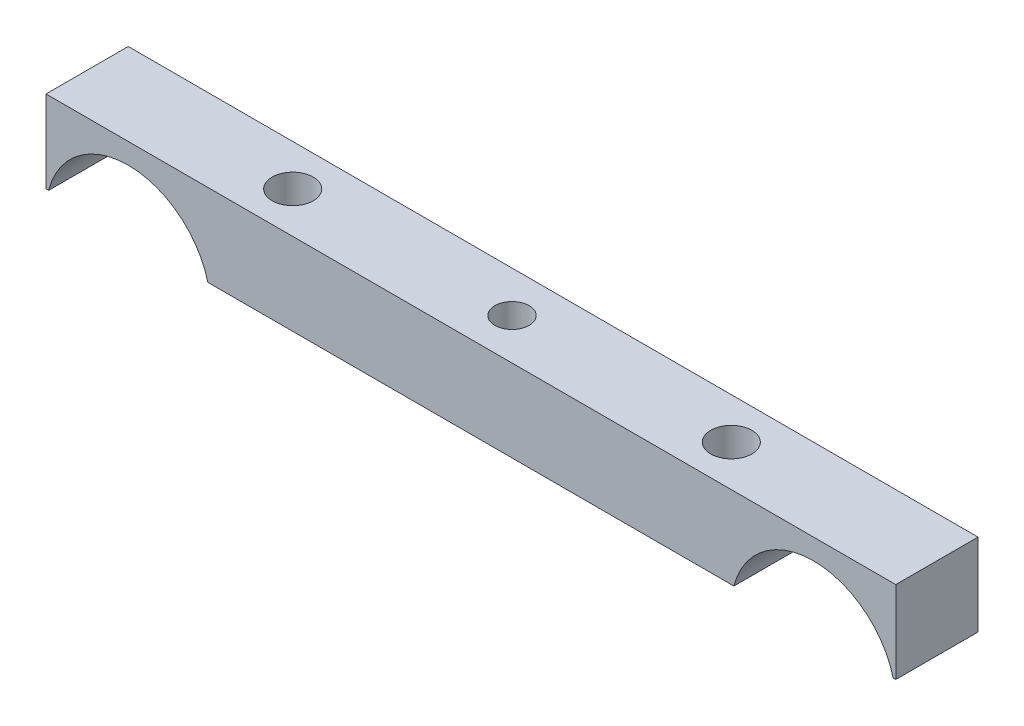
SolidWorks part; units mm, degrees
material "Delrin 2700 NC010, copolymère d'acétal à faible viscosité (SS)"
ref_plane "Plan de face" through (0, 0, 0) normal (0, 0, 1) x (1, 0, 0)
ref_plane "Plan de dessus" through (0, 0, 0) normal (0, 1, 0) x (1, 0, 0)
ref_plane "Plan de droite" through (0, 0, 0) normal (1, 0, 0) x (0, 0, -1)
sketch "Esquisse1" plane through (0, 0, 0) normal (0, 0, 1) x (1, 0, 0)
  line L0 (-31, 1.5) -> (-31, 7.5)
  line L1 (-31, 7.5) -> (31, 7.5)
  line L2 (31, 7.5) -> (31, 1.5)
  line L3 (31, 1.5) -> (30.8095, 1.5)
  line L4 (-30.8095, 1.5) -> (-31, 1.5)
  line L5 (-19.1905, 1.5) -> (19.1905, 1.5)
  arc A0 (-19.1905, 1.5) -> (-30.8095, 1.5) centre (-25, 0) ccw
  arc A1 (19.1905, 1.5) -> (30.8095, 1.5) centre (25, 0) cw
  dimension "D1" = 0
  dimension "D3" = 1.5
  dimension "D5" = 62
  dimension "D6" = 6
  dimension "D7" = 6
  dimension "D2" = 0
  dimension "D4" = 6
  dimension "D8" = 31
extrude "Boss.-Extru.1" add sketch "Esquisse1" along normal blind 6
sketch "Esquisse2" plane through (0, 7.5, 0) normal (0, 1, 0) x (1, 0, 0)
  circle A0 centre (-16, -3) radius 1.5
  circle A1 centre (16, -3) radius 1.5
  circle A2 centre (0, -3) radius 1.25
  dimension "D1" = 3
  dimension "D2" = 2.5
  dimension "D3" = 3
extrude "Enlèv. mat.-Extru.1" cut sketch "Esquisse2" against normal blind 6
